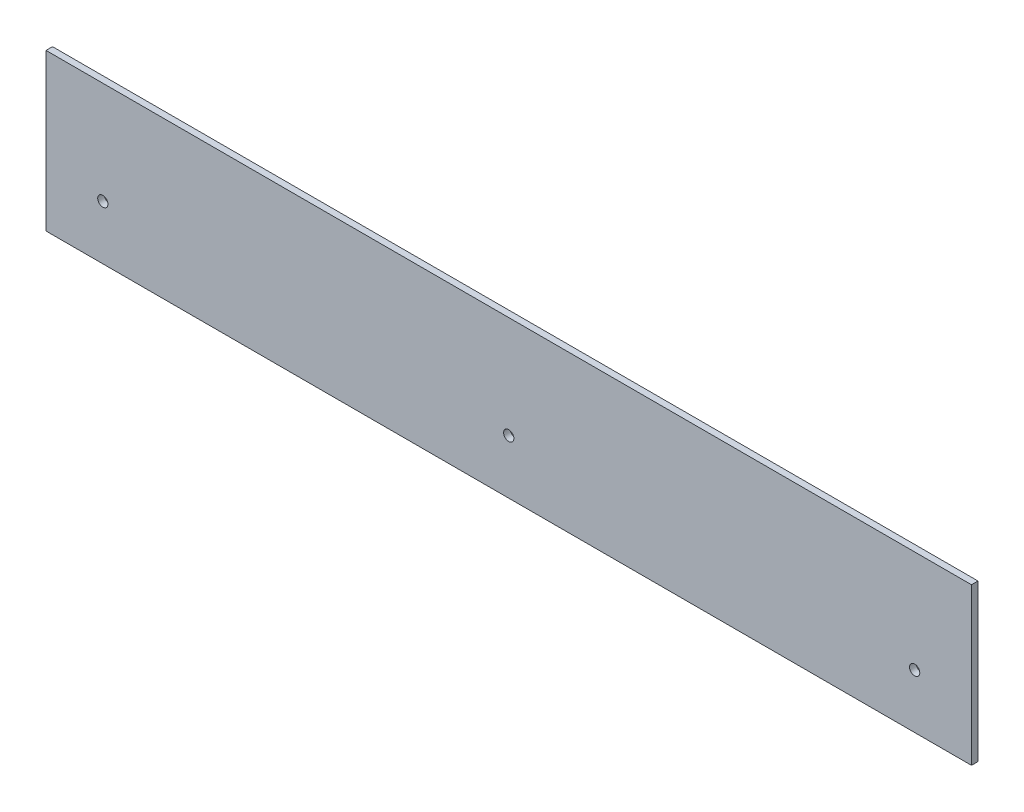
SolidWorks part; units mm, degrees
ref_plane "Front" through (0, 0, 0) normal (0, 0, 1) x (1, 0, 0)
ref_plane "Top" through (0, 0, 0) normal (0, 1, 0) x (1, 0, 0)
ref_plane "Right" through (0, 0, 0) normal (1, 0, 0) x (0, 0, -1)
sketch "Sketch1" plane through (0, 0, 0) normal (0, 0, 1) x (1, 0, 0)
  line L1 (-225.425, 38.1) -> (225.425, 38.1)
  line L2 (-225.425, 38.1) -> (-225.425, -38.1)
  line L3 (-225.425, -38.1) -> (225.425, -38.1)
  line L4 (225.425, 38.1) -> (225.425, -38.1)
  line L5 (-225.425, 38.1) -> (225.425, -38.1) construction
  line L6 (-225.425, -38.1) -> (225.425, 38.1) construction
  point P0 (0, 0)
  dimension "D1" = 450.85
  dimension "D2" = 76.2
extrude "Boss-Extrude1" add sketch "Sketch1" along normal blind 3.175
sketch "Sketch2" plane through (0, 0, 3.175) normal (0, 0, 1) x (1, 0, 0)
  line L0 (0, -1.7463) -> (0, 1.7463) construction
  line L4 (225.425, -38.1) -> (225.425, 38.1)
  line L5 (225.425, 38.1) -> (-225.425, 38.1)
  line L6 (-225.425, 38.1) -> (-225.425, -38.1)
  line L7 (-225.425, -38.1) -> (225.425, -38.1)
  line L8 (225.425, -38.1) -> (225.425, 38.1)
  line L9 (225.425, 38.1) -> (-225.425, 38.1)
  line L10 (-225.425, 38.1) -> (-225.425, -38.1)
  line L11 (-225.425, -38.1) -> (225.425, -38.1)
  circle A0 centre (-197.739, -11.684) radius 2.5
  circle A1 centre (197.739, -11.684) radius 2.5
  circle A2 centre (0, -11.684) radius 2.5
  dimension "D2" = 5
  dimension "D3" = 27.686
  dimension "D4" = 26.416
  dimension "D5" = 5
  dimension "D6" = 26.416
  dimension "D1" = 0
extrude "Cut-Extrude1" cut sketch "Sketch2" against normal through all contours A0 | A1 | A2
